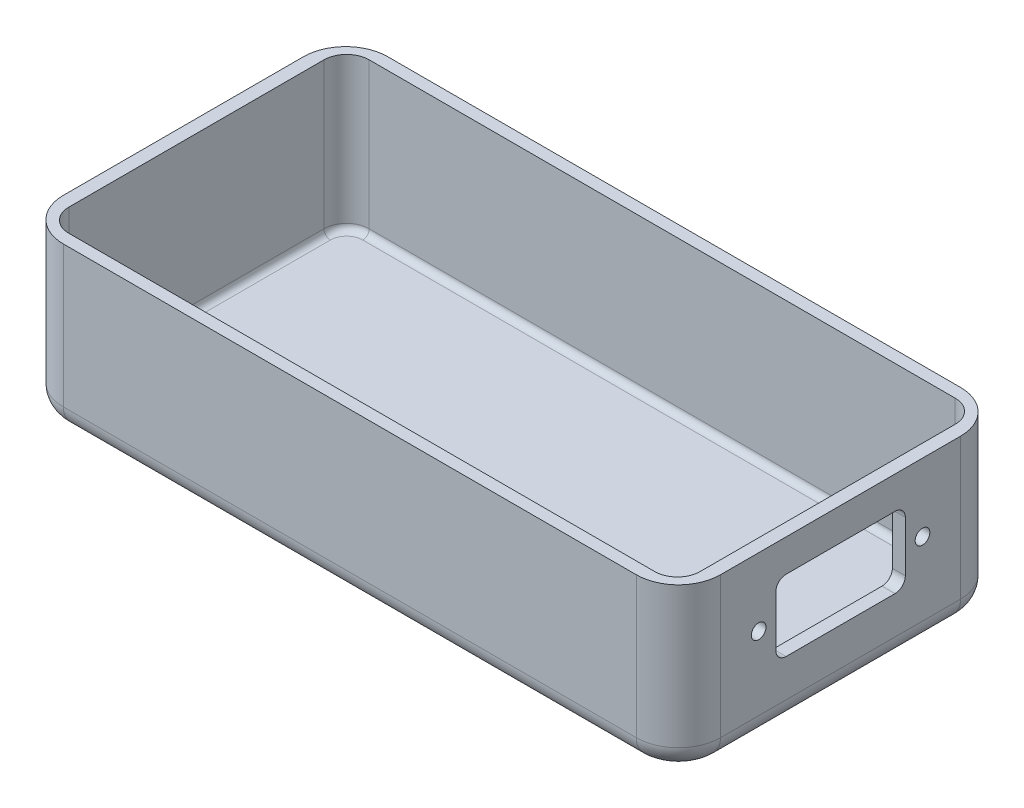
SolidWorks part; units mm, degrees
ref_plane "Front Plane" through (0, 0, 0) normal (0, 0, 1) x (1, 0, 0)
ref_plane "Top Plane" through (0, 0, 0) normal (0, 1, 0) x (1, 0, 0)
ref_plane "Right Plane" through (0, 0, 0) normal (1, 0, 0) x (0, 0, -1)
sketch "Sketch1" plane through (0, 0, 0) normal (0, 1, 0) x (1, 0, 0)
  line L1 (-50.75, 25.05) -> (50.75, 25.05)
  line L2 (-50.75, 25.05) -> (-50.75, -25.05)
  line L3 (-50.75, -25.05) -> (50.75, -25.05)
  line L4 (50.75, 25.05) -> (50.75, -25.05)
  line L5 (-50.75, 25.05) -> (50.75, -25.05) construction
  line L6 (-50.75, -25.05) -> (50.75, 25.05) construction
  point P0 (0, 0)
  dimension "D1" = 101.5
  dimension "D2" = 50.1
extrude "Boss-Extrude1" add sketch "Sketch1" along normal blind 25.3
fillet "Fillet1" radius 6.5 4 edges at (-50.75, 12.65, -25.05) (50.75, 12.65, -25.05) (-50.75, 12.65, 25.05) (50.75, 12.65, 25.05)
fillet "Fillet2" radius 3.5 8 edges at (-48.8462, 0, 23.1462) (0, 0, 25.05) (48.8462, 0, 23.1462) (50.75, 0, 0) (48.8462, 0, -23.1462) (0, 0, -25.05) (-48.8462, 0, -23.1462) (-50.75, 0, 0)
sketch "Sketch2" plane through (0, 25.3, 0) normal (0, 1, 0) x (1, 0, 0)
  line L1 (-45.25, 23.2) -> (45.25, 23.2)
  line L2 (-48.75, 19.7) -> (-48.75, -19.7)
  line L3 (-45.25, -23.2) -> (45.25, -23.2)
  line L4 (48.75, 19.7) -> (48.75, -19.7)
  line L5 (-48.75, 23.2) -> (48.75, -23.2) construction
  line L6 (-48.75, -23.2) -> (48.75, 23.2) construction
  arc A0 (45.25, 23.2) -> (48.75, 19.7) centre (45.25, 19.7) cw
  arc A1 (45.25, -23.2) -> (48.75, -19.7) centre (45.25, -19.7) ccw
  arc A2 (-48.75, -19.7) -> (-45.25, -23.2) centre (-45.25, -19.7) ccw
  arc A3 (-45.25, 23.2) -> (-48.75, 19.7) centre (-45.25, 19.7) ccw
  point P0 (0, 0)
  dimension "D3" = 3.5
  dimension "D1" = 97.5
  dimension "D2" = 46.4
extrude "Cut-Extrude1" cut sketch "Sketch2" against normal blind 23.6
fillet "Fillet3" radius 1 8 edges at (48.75, 1.7, 0) (47.7249, 1.7, 22.1749) (0, 1.7, 23.2) (-47.7249, 1.7, 22.1749) (-48.75, 1.7, 0) (-47.7249, 1.7, -22.1749) (0, 1.7, -23.2) (47.7249, 1.7, -22.1749)
sketch "Sketch3" plane through (48.75, 0, 0) normal (-1, 0, 0) x (0, 0, 1)
  line L4 (-10, 20.3) -> (-10, 9.3)
  line L5 (-10, 9.3) -> (10, 9.3)
  line L6 (10, 9.3) -> (10, 20.3)
  line L7 (10, 20.3) -> (-10, 20.3)
  line L8 (-10, 20.3) -> (-10, 9.3)
  line L9 (-10, 9.3) -> (10, 9.3)
  line L10 (10, 9.3) -> (10, 20.3)
  line L11 (10, 20.3) -> (-10, 20.3)
  dimension "D1" = 0
extrude "Cut-Extrude2" cut sketch "Sketch3" against normal up to next
hole_wizard "Tap Drill for #4-40 Tap1" positions "Sketch5" profile "Sketch4" hole size "#4-40" standard "Ansi Inch"
sketch "Sketch5" plane through (50.75, 0, 0) normal (1, 0, 0) x (0, 0, -1)
  circle A0 centre (-12.65, 14.8) radius 1.5 construction
  point P0 (-12.65, 14.8)
  point P1 (12.65, 14.8)
sketch "Sketch4" plane through (50.75, 14.8, 12.65) normal (0, 1, 0) x (0, 0, -1)
  line L0 (0, 0) -> (0, 2)
  line L1 (0, 2) -> (1.1303, 2)
  line L2 (1.1303, 2) -> (1.1303, 0)
  line L5 (1.1303, 0) -> (0, 0)
  line L11 (0, -6.35) -> (0, 107.95) construction
  dimension "Thru Hole Dia." = 2.2606
  dimension "Thru Hole Depth" = 2
fillet "1/8\" end mill" radius 1.5875 4 edges at (49.75, 20.3, -10) (49.75, 20.3, 10) (49.75, 9.3, 10) (49.75, 9.3, -10)
